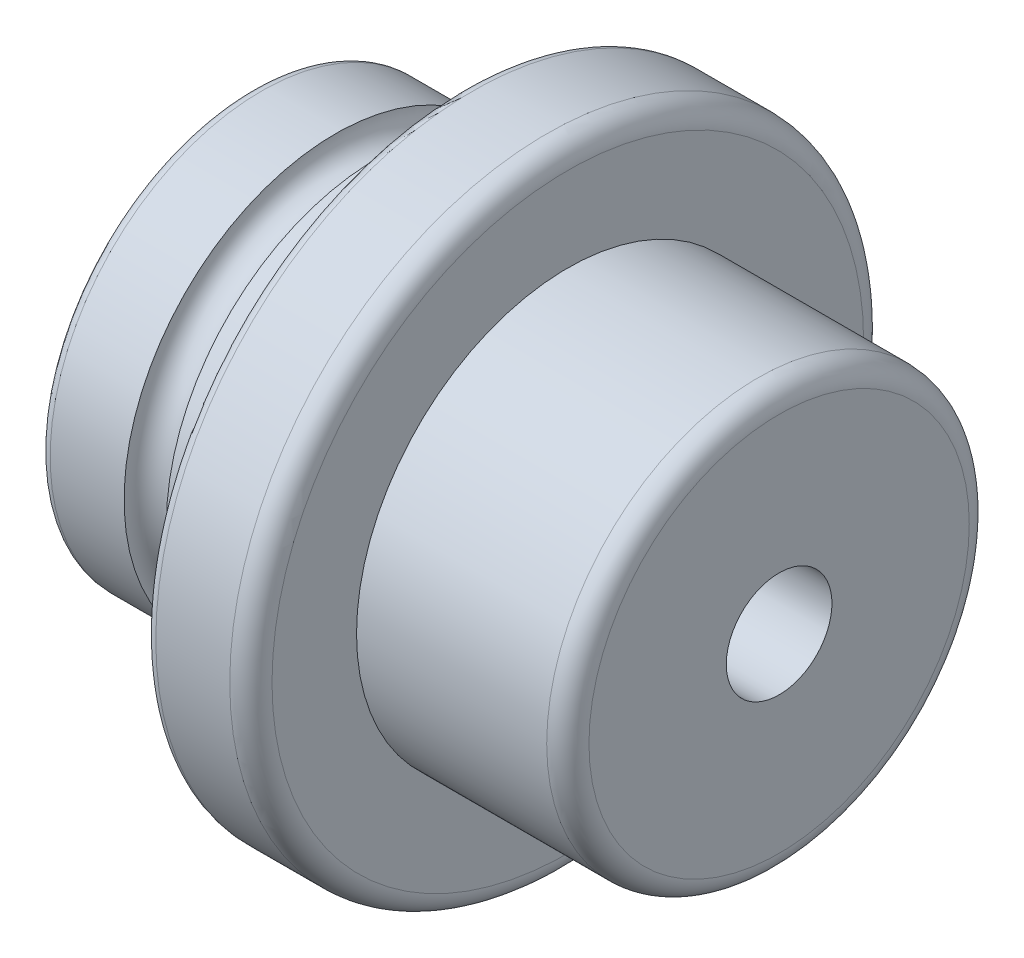
SolidWorks part; units mm, degrees
ref_plane "Přední rovina" through (0, 0, 0) normal (0, 0, 1) x (1, 0, 0)
ref_plane "Horní rovina" through (0, 0, 0) normal (0, 1, 0) x (1, 0, 0)
ref_plane "Pravá rovina" through (0, 0, 0) normal (1, 0, 0) x (0, 0, -1)
sketch "Skica1" plane through (0, 0, 0) normal (0, 0, 1) x (1, 0, 0)
  line L0 (0, 0) -> (54.964, 0) construction
  line L1 (0, 5) -> (50, 5)
  line L2 (50, 5) -> (50, 20)
  line L3 (50, 20) -> (30, 20)
  line L4 (30, 20) -> (30, 30)
  line L5 (30, 30) -> (20, 30)
  line L6 (20, 30) -> (20, 20)
  line L7 (20, 20) -> (0, 20)
  line L8 (0, 20) -> (0, 5)
  point P5 (20, 25)
  dimension "D1" = 50
  dimension "D2" = 20
  dimension "D3" = 10
  dimension "D4" = 10
  dimension "D5" = 40
  dimension "D6" = 60
revolve "Rotovat1" add sketch "Skica1" angle 360 about L0
sketch "Skica2" plane through (0, 0, 0) normal (0, 0, 1) x (1, 0, 0)
  line L0 (20, 20) -> (0, 20) construction
  line L1 (20, 30) -> (20, -30) construction
  circle A0 centre (10, 20) radius 2
  dimension "D1" = 4
  dimension "D2" = 10
revolve "Odebrat rotací1" cut sketch "Skica2" angle 360 about axis through (0, 0, 0) along (-1, 0, 0)
fillet "Zaoblit8" radius 1 1 edges at (0, 0, 20)
fillet "Zaoblit9" radius 1 1 edges at (20, 0, 30)
fillet "Zaoblit10" radius 2 1 edges at (30, 0, 30)
fillet "Zaoblit11" radius 2 1 edges at (50, 0, 20)
